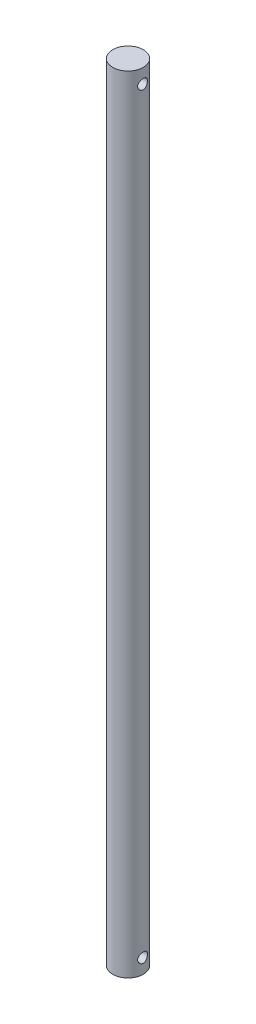
SolidWorks part; units mm, degrees
ref_plane "Front Plane" through (0, 0, 0) normal (0, 0, 1) x (1, 0, 0)
ref_plane "Top Plane" through (0, 0, 0) normal (0, 1, 0) x (1, 0, 0)
ref_plane "Right Plane" through (0, 0, 0) normal (1, 0, 0) x (0, 0, -1)
sketch "Sketch1" plane through (0, 0, 0) normal (0, 1, 0) x (1, 0, 0)
  circle A0 centre (0, 0) radius 9.906
  dimension "D1" = 19.812
extrude "Boss-Extrude1" add sketch "Sketch1" along normal blind 508
sketch "Sketch2" plane through (0, 0, 0) normal (1, 0, 0) x (0, 0, -1)
  line L0 (9.906, 508) -> (-9.906, 508) construction
  line L6 (-9.906, 508) -> (-9.906, 0) construction
  circle A0 centre (0, 498.602) radius 3.175
  dimension "D2" = 6.35
  dimension "D1" = 9.398
  dimension "D3" = 9.906
extrude "Cut-Extrude1" cut sketch "Sketch2" against normal blind 22.86 from offset 20.32
ref_plane "Plane1" through (0, 254, 0) normal (0, 1, 0) x (1, 0, 0)
mirror "Mirror1" about plane through (0, 254, 0) normal (0, 1, 0) of "Cut-Extrude1"
scale "Scale1" scale about centroid uniform scaling yes scale factor 0.25
